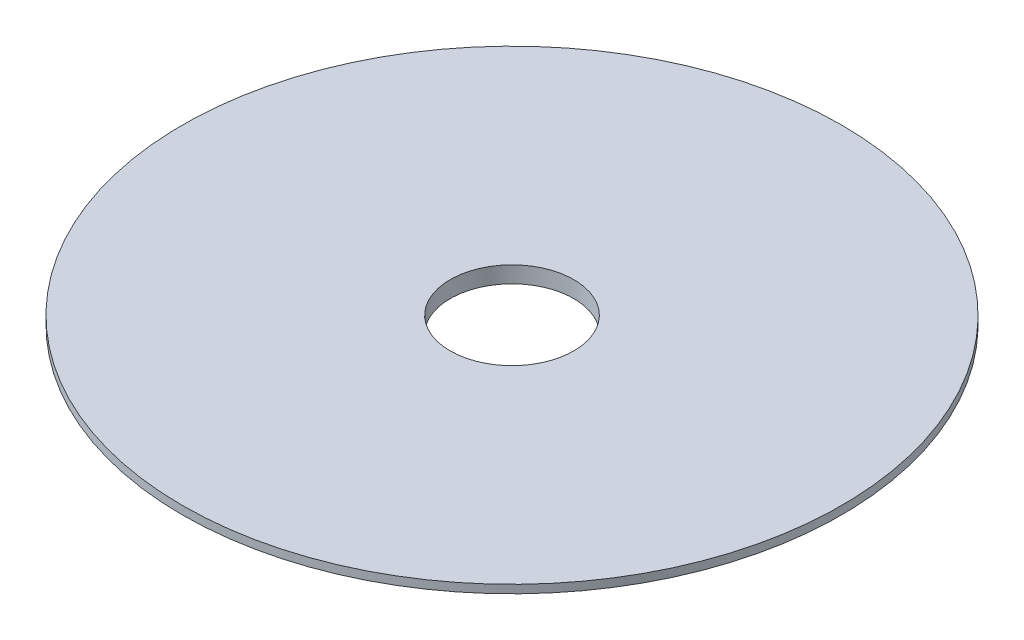
SolidWorks part; units mm, degrees
ref_plane "前视基准面" through (0, 0, 0) normal (0, 0, 1) x (1, 0, 0)
ref_plane "上视基准面" through (0, 0, 0) normal (0, 1, 0) x (1, 0, 0)
ref_plane "右视基准面" through (0, 0, 0) normal (1, 0, 0) x (0, 0, -1)
sketch "草图1" plane through (0, 0, 0) normal (0, 1, 0) x (1, 0, 0)
  circle A0 centre (0, 0) radius 22.5
  dimension "D1" = 45
extrude "凸台-拉伸1" add sketch "草图1" along normal blind 1
sketch "草图2" plane through (0, 1, 0) normal (0, 1, 0) x (1, 0, 0)
  circle A0 centre (0, 0) radius 40
  dimension "D1" = 80
extrude "凸台-拉伸2" add sketch "草图2" along normal blind 1
sketch "草图3" plane through (0, 2, 0) normal (0, 1, 0) x (1, 0, 0)
  circle A0 centre (0, 0) radius 7.5
  dimension "D1" = 15
extrude "切除-拉伸1" cut sketch "草图3" against normal blind 500
sketch "草图4" plane through (0, 2, 0) normal (0, 1, 0) x (1, 0, 0)
  circle A0 centre (-25.8626, 123.3339) radius 1.5
  circle A1 centre (-31.6821, 109.4046) radius 1.5
  circle A2 centre (-23.5539, 96.6837) radius 1.5
sketch "草图5" plane through (0, 0, 0) normal (0, -1, 0) x (1, 0, 0)
  circle A0 centre (0, 0) radius 22.5
  circle A1 centre (0, 0) radius 15
  dimension "D1" = 30
extrude "切除-拉伸3" cut sketch "草图5" against normal up to surface (1 mm away) up to face at (0, 1, 22.5)
